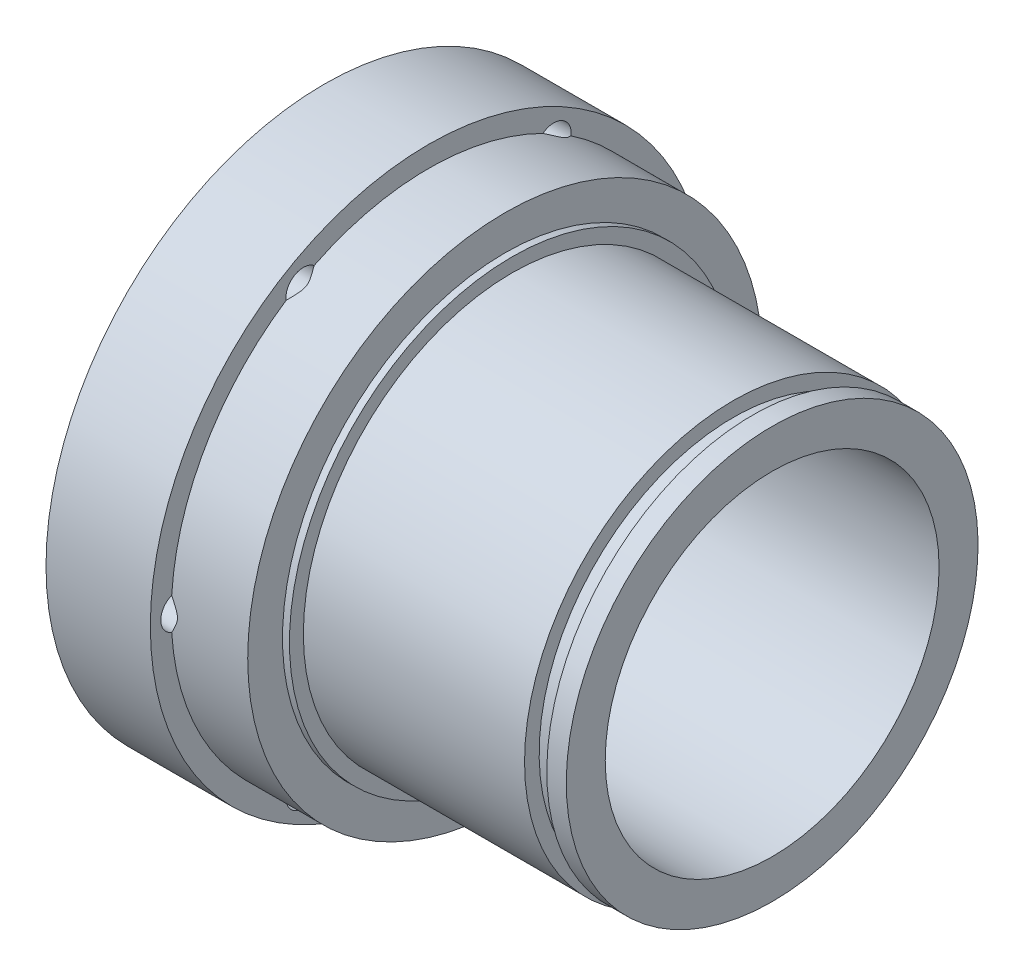
SolidWorks part; units mm, degrees
material "5052-H32"
ref_plane "Front Plane" through (0, 0, 0) normal (0, 0, 1) x (1, 0, 0)
ref_plane "Top Plane" through (0, 0, 0) normal (0, 1, 0) x (1, 0, 0)
ref_plane "Right Plane" through (0, 0, 0) normal (1, 0, 0) x (0, 0, -1)
sketch "Sketch1" plane through (0, 0, 0) normal (0, 0, 1) x (1, 0, 0)
  line L0 (-3.7084, 0) -> (3.7084, 0) construction
  line L1 (0, 16) -> (0, 20)
  line L2 (0, 20) -> (7.5, 20)
  line L3 (0, 20) -> (7.5, 20) construction
  line L4 (7.5, 20) -> (7.5, 18.5)
  line L5 (7.5, 18.5) -> (13, 18.5)
  line L6 (13, 18.5) -> (13, 16)
  line L7 (13, 16) -> (13.5, 16)
  line L8 (13.5, 16) -> (13.5, 15)
  line L9 (13.5, 15) -> (29.4, 15)
  line L10 (29.4, 15) -> (29.4, 13.95)
  line L11 (29.4, 13.95) -> (30.8, 13.95)
  line L12 (30.8, 13.95) -> (30.8, 14.8)
  line L13 (30.8, 14.8) -> (32.2, 14.8)
  line L14 (32.2, 14.8) -> (32.2, 12)
  line L15 (32.2, 12) -> (7, 12)
  line L16 (7, 12) -> (7, 15)
  line L17 (7, 15) -> (6.5, 15)
  line L18 (6.5, 15) -> (6.5, 16)
  line L19 (6.5, 16) -> (0, 16)
  line L20 (29.5, 13.95) -> (29.5, 15.4308) construction
revolve "Revolve1" add sketch "Sketch1" angle 360 about L0
hole_wizard "M3 Tapped Hole1" positions "Sketch2" profile "Sketch4" tap size "M3" standard "ISO"
sketch "Sketch2" plane through (0, 0, 0) normal (-1, 0, 0) x (0, 0, 1)
  point P0 (18, 0)
sketch "Sketch4" plane through (0, 0, 18) normal (0, 1, 0) x (0, 0, 1)
  line L0 (0, 0) -> (0, 8.2511)
  line L1 (0, 8.2511) -> (1.25, 7.5)
  line L2 (1.25, 7.5) -> (1.25, 0)
  line L5 (1.25, 0) -> (0, 0)
  line L10 (0, 8.2511) -> (-1.25, 7.5) construction
  line L11 (0, -6.35) -> (0, 107.95) construction
  dimension "Tap Drill Dia." = 2.5
  dimension "Tap Drill Depth" = 7.5
  dimension "Drill Angle" = 118
cosmetic thread "Hole Thread1"
pattern_circular "CirPattern1" count 6 over 360 about axis through (0, 0, 0) along (1, 0, 0) of "M3 Tapped Hole1"
cosmetic thread "Hole Thread2"
cosmetic thread "Hole Thread3"
cosmetic thread "Hole Thread4"
cosmetic thread "Hole Thread5"
cosmetic thread "Hole Thread6"
